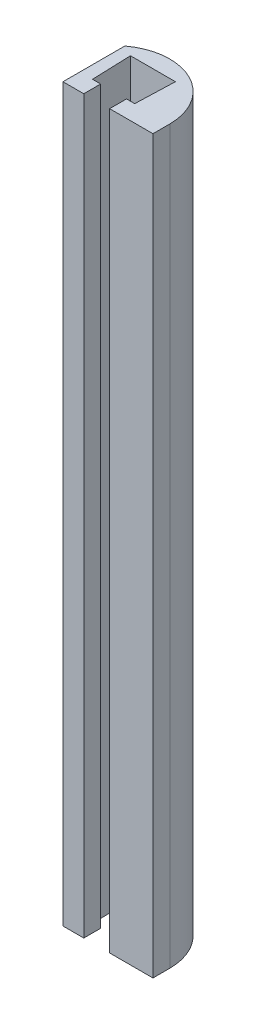
SolidWorks part; units mm, degrees
ref_plane "Front" through (0, 0, 0) normal (0, 0, 1) x (1, 0, 0)
ref_plane "Top" through (0, 0, 0) normal (0, 1, 0) x (1, 0, 0)
ref_plane "Right" through (0, 0, 0) normal (1, 0, 0) x (0, 0, -1)
sketch "Skizze1" plane through (0, 0, 0) normal (0, 1, 0) x (1, 0, 0)
  line L0 (2.3, 0) -> (10, 0)
  line L1 (0, 0) -> (0, 23.1618) construction
  line L2 (10, 0) -> (10, 3)
  line L3 (3.75, 3) -> (2.3, 3)
  line L4 (2.3, 3) -> (2.3, 0)
  line L5 (-3.75, 3) -> (-2.3, 3)
  line L6 (-6, 0) -> (-6, 11)
  line L7 (-2.3, 0) -> (-6, 0)
  line L8 (-2.3, 3) -> (-2.3, 0)
  line L9 (3.75, 3) -> (4, 10)
  line L10 (4, 10) -> (-4, 10)
  line L11 (-3.75, 3) -> (-4, 10)
  line L13 (10, 3) -> (3.75, 3) construction
  arc A0 (10, 3) -> (0, 13) centre (0, 3) ccw
  arc A1 (-6, 11) -> (0, 13) centre (0, 3) cw
  point P20 (0, 10)
  dimension "D1" = 10
  dimension "D2" = 4.6
  dimension "D3" = 3
  dimension "D4" = 8
  dimension "D5" = 7.5
  dimension "D6" = 7
  dimension "D7" = 6
extrude "Aufsatz-Linear austragen1" add sketch "Skizze1" along normal blind 130
sketch "Skizze2" plane through (0, 0, -3) normal (0, 0, -1) x (-1, 0, 0)
  line L0 (0, 0) -> (0, 130) construction
  line L1 (6, 130) -> (-10, 130) construction
  line L2 (-10, 0) -> (6, 0) construction
  circle A0 centre (0, 14) radius 3.75
  dimension "D1" = 7.5
  dimension "D2" = 14
extrude "Schnitt-Linear austragen1" cut sketch "Skizze2" along normal through all
